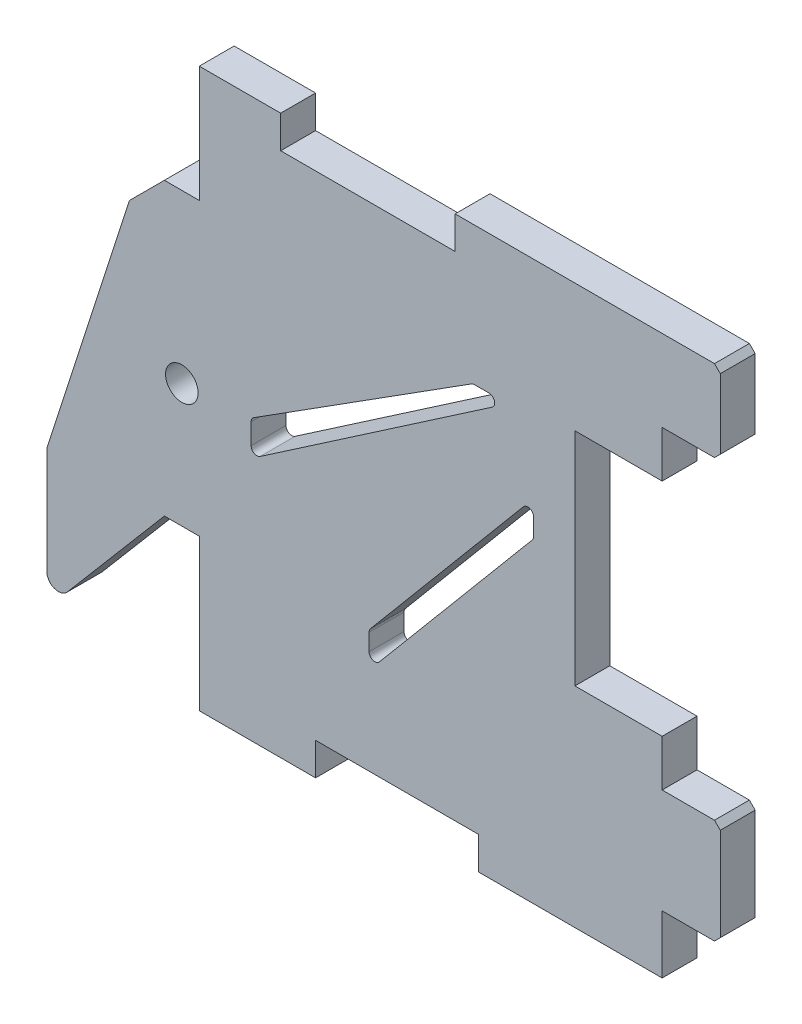
SolidWorks part; units mm, degrees
ref_plane "前视基准面" through (0, 0, 0) normal (0, 0, 1) x (1, 0, 0)
ref_plane "上视基准面" through (0, 0, 0) normal (0, 1, 0) x (1, 0, 0)
ref_plane "右视基准面" through (0, 0, 0) normal (1, 0, 0) x (0, 0, -1)
sketch "草图1" plane through (0, 0, 0) normal (0, 0, 1) x (1, 0, 0)
  line L1 (3.4995, 9.537) -> (-15.2099, -2.3308)
  line L3 (-14.6598, -4.9429) -> (5.2879, 8.7021)
  line L5 (-15.4421, -2.753) -> (-15.4421, -4.5302)
  line L7 (5.0056, 9.6148) -> (3.7673, 9.6148)
  line L9 (7.9669, 2.6231) -> (-5.1808, -13.0337)
  line L11 (8.8498, 0.8566) -> (8.8498, 2.3015)
  line L13 (-4.415, -15.1218) -> (8.7327, 0.535)
  line L15 (-5.2979, -13.3553) -> (-5.2979, -14.8002)
  line L48 (24.9, -12.5) -> (15.9, -12.5)
  line L49 (15.9, -12.5) -> (15.9, 14.5)
  line L50 (15.9, 14.5) -> (24.9, 14.5)
  line L51 (24.9, 14.5) -> (24.9, 21.5)
  line L52 (24.9, 21.5) -> (2.1, 21.5)
  line L53 (2.1, 21.5) -> (2.1, 18.7)
  line L54 (2.1, 18.7) -> (-12.9, 18.7)
  line L55 (-12.9, 18.7) -> (-12.9, 21.5)
  line L56 (-12.9, 21.5) -> (-19.9, 21.5)
  line L57 (-19.9, 21.5) -> (-19.9, 11.5)
  line L58 (-19.9, 11.5) -> (-22.9, 11.5)
  line L59 (-22.9, 11.5) -> (-25.9, 8.5)
  line L60 (-25.9, 8.5) -> (-25.9, -10.5)
  line L61 (-25.9, -10.5) -> (-22.9, -13.5)
  line L62 (-22.9, -13.5) -> (-19.9, -13.5)
  line L63 (-19.9, -13.5) -> (-19.9, -26.5)
  line L64 (-19.9, -26.5) -> (-9.9, -26.5)
  line L65 (-9.9, -26.5) -> (-9.9, -23.7)
  line L66 (-9.9, -23.7) -> (4.1, -23.7)
  line L67 (4.1, -23.7) -> (4.1, -26.5)
  line L68 (4.1, -26.5) -> (19.9, -26.5)
  line L69 (19.9, -26.5) -> (19.9, -21.5)
  line L70 (19.9, -21.5) -> (24.9, -21.5)
  line L71 (24.9, -21.5) -> (24.9, -12.5)
  circle A1 centre (-21.4, -1.0533) radius 1.8
  arc A3 (-15.2099, -2.3308) -> (-15.4421, -2.753) centre (-14.9421, -2.753) ccw
  arc A5 (-15.4421, -4.5302) -> (-14.6598, -4.9429) centre (-14.9421, -4.5302) ccw
  arc A7 (3.7673, 9.6148) -> (3.4995, 9.537) centre (3.7673, 9.1148) ccw
  arc A9 (5.2879, 8.7021) -> (5.0056, 9.6148) centre (5.0056, 9.1148) ccw
  arc A11 (8.8498, 2.3015) -> (7.9669, 2.6231) centre (8.3498, 2.3015) ccw
  arc A13 (8.7327, 0.535) -> (8.8498, 0.8566) centre (8.3498, 0.8566) ccw
  arc A15 (-5.1808, -13.0337) -> (-5.2979, -13.3553) centre (-4.7979, -13.3553) ccw
  arc A17 (-5.2979, -14.8002) -> (-4.415, -15.1218) centre (-4.7979, -14.8002) ccw
extrude "凸台-拉伸1" add sketch "草图1" along normal blind 3
ref_plane "基准面1" through (15.9, 14.5, 3) normal (1, 0, 0) x (0, 0, -1)
sketch "草图2" plane through (15.9, 0, 0) normal (1, 0, 0) x (0, 0, -1)
  line L4 (0, -12.5) -> (0, 14.5)
  line L5 (0, 14.5) -> (-3, 14.5)
  line L6 (-3, 14.5) -> (-3, -12.5)
  line L7 (-3, -12.5) -> (0, -12.5)
  line L8 (0, -12.5) -> (0, 14.5)
  line L9 (0, 14.5) -> (-3, 14.5)
  line L10 (-3, 14.5) -> (-3, -12.5)
  line L11 (-3, -12.5) -> (0, -12.5)
  dimension "D1" = 0
extrude "切除-拉伸1" cut sketch "草图2" against normal blind 2
sketch "草图3" plane through (0, 14.5, 0) normal (0, -1, 0) x (1, 0, 0)
  line L1 (19.9, 0) -> (19.9, 3)
  line L4 (13.9, 0) -> (24.9, 0)
  line L5 (24.9, 0) -> (24.9, 3)
  line L6 (24.9, 3) -> (13.9, 3)
  line L7 (13.9, 3) -> (13.9, 0)
  line L8 (13.9, 0) -> (19.9, 0)
  line L10 (19.9, 3) -> (13.9, 3)
  line L11 (13.9, 3) -> (13.9, 0)
  dimension "D1" = 0
extrude "凸台-拉伸2" add sketch "草图3" along normal blind 5
sketch "草图4" plane through (0, -12.5, 0) normal (0, 1, 0) x (1, 0, 0)
  line L1 (19.9, -3) -> (19.9, 0)
  line L4 (24.9, 0) -> (13.9, 0)
  line L5 (13.9, 0) -> (13.9, -3)
  line L6 (13.9, -3) -> (24.9, -3)
  line L7 (24.9, -3) -> (24.9, 0)
  line L8 (19.9, 0) -> (13.9, 0)
  line L9 (13.9, 0) -> (13.9, -3)
  line L10 (13.9, -3) -> (19.9, -3)
  dimension "D1" = 0
extrude "凸台-拉伸3" add sketch "草图4" along normal blind 5
sketch "草图5" plane through (0, -7.5, 0) normal (0, 1, 0) x (1, 0, 0)
  line L4 (13.9, 0) -> (13.9, -3)
  line L5 (13.9, -3) -> (19.9, -3)
  line L6 (19.9, -3) -> (19.9, 0)
  line L7 (19.9, 0) -> (13.9, 0)
  line L8 (13.9, 0) -> (13.9, -3)
  line L9 (13.9, -3) -> (19.9, -3)
  line L10 (19.9, -3) -> (19.9, 0)
  line L11 (19.9, 0) -> (13.9, 0)
  dimension "D1" = 0
extrude "切除-拉伸2" cut sketch "草图5" against normal blind 1
sketch "草图6" plane through (0, 9.5, 0) normal (0, -1, 0) x (1, 0, 0)
  line L4 (13.9, 3) -> (13.9, 0)
  line L5 (13.9, 0) -> (19.9, 0)
  line L6 (19.9, 0) -> (19.9, 3)
  line L7 (19.9, 3) -> (13.9, 3)
  line L8 (13.9, 3) -> (13.9, 0)
  line L9 (13.9, 0) -> (19.9, 0)
  line L10 (19.9, 0) -> (19.9, 3)
  line L11 (19.9, 3) -> (13.9, 3)
  dimension "D1" = 0
extrude "切除-拉伸3" cut sketch "草图6" against normal blind 1
sketch "草图8" plane through (13.9, 0, 0) normal (1, 0, 0) x (0, 0, -1)
  line L4 (-3, 10.5) -> (-3, -8.5)
  line L5 (-3, -8.5) -> (0, -8.5)
  line L6 (0, -8.5) -> (0, 10.5)
  line L7 (0, 10.5) -> (-3, 10.5)
  line L8 (-3, 10.5) -> (-3, -8.5)
  line L9 (-3, -8.5) -> (0, -8.5)
  line L10 (0, -8.5) -> (0, 10.5)
  line L11 (0, 10.5) -> (-3, 10.5)
  dimension "D1" = 0
extrude "切除-拉伸4" cut sketch "草图8" against normal blind 1.5
sketch "草图9" plane through (0, 0, 3) normal (0, 0, 1) x (1, 0, 0)
  line L2 (-22.9, 11.5) -> (-34.017, 11.5)
  line L4 (-22.9, 11.5) -> (-25.9, 8.5) construction
  line L5 (-22.9, 11.5) -> (-25.9, 8.5)
  line L6 (-25.9, 8.5) -> (-25.9, -10.5) construction
  line L7 (-25.9, 8.5) -> (-25.9, -10.5)
  line L8 (-25.9, -10.5) -> (-22.9, -13.5) construction
  line L9 (-25.9, -10.5) -> (-22.9, -13.5)
  line L10 (-44.7054, -27.9916) -> (-44.7054, -32.9916)
  line L11 (-22.9, -13.5) -> (-44.7054, -32.9916)
  line L12 (-44.7054, -27.9916) -> (-44.7054, -17.9916)
  line L13 (-44.7054, -17.9916) -> (-34.017, 11.5)
extrude "凸台-拉伸4" [suppressed] add sketch "草图9" against normal up to surface (3 mm away)
fillet "圆角1" [suppressed] radius 2
sketch "草图10" plane through (0, 0, 3) normal (0, 0, 1) x (1, 0, 0)
  line L0 (-25.9, -10.5) -> (-22.9, -13.5) construction
  line L1 (-25.9, -10.5) -> (-22.9, -13.5)
  line L2 (-25.9, 8.5) -> (-25.9, -10.5) construction
  line L3 (-25.9, 8.5) -> (-25.9, -10.5)
  line L6 (-22.9, -13.5) -> (-33.0082, -25.403)
  line L7 (-25.9, 8.5) -> (-33.0082, -13.5)
  line L8 (-33.0082, -13.5) -> (-33.0082, -25.403)
extrude "凸台-拉伸5" add sketch "草图10" against normal up to surface (3 mm away) up to face at (1.1929, -2.5357, 0)
fillet "圆角2" radius 1 1 edges at (-33.0082, -25.403, 1.5)
chamfer "倒角1" distance 0.5 angle 45 4 edges at (24.9, -21.5, 1.5) (24.9, -12.5, 1.5) (24.9, 14.5, 1.5) (24.9, 21.5, 1.5)
sketch "草图11" plane through (0, 0, 3) normal (0, 0, 1) x (1, 0, 0)
  circle A0 centre (-21.4, -1.0533) radius 1.8 construction
  circle A1 centre (-21.4, -1.0533) radius 1.8
extrude "凸台-拉伸6" add sketch "草图11" against normal up to surface (3 mm away) up to face at (1.7474, -3.4889, 0)
extrude "切除-拉伸5" cut sketch "草图12" against normal blind 3
sketch "草图12" plane through (175.8432, -50.8725, 3) normal (0, 0, 1) x (1, 0, 0)
  circle A0 centre (-197.2432, 47.9871) radius 1.4
